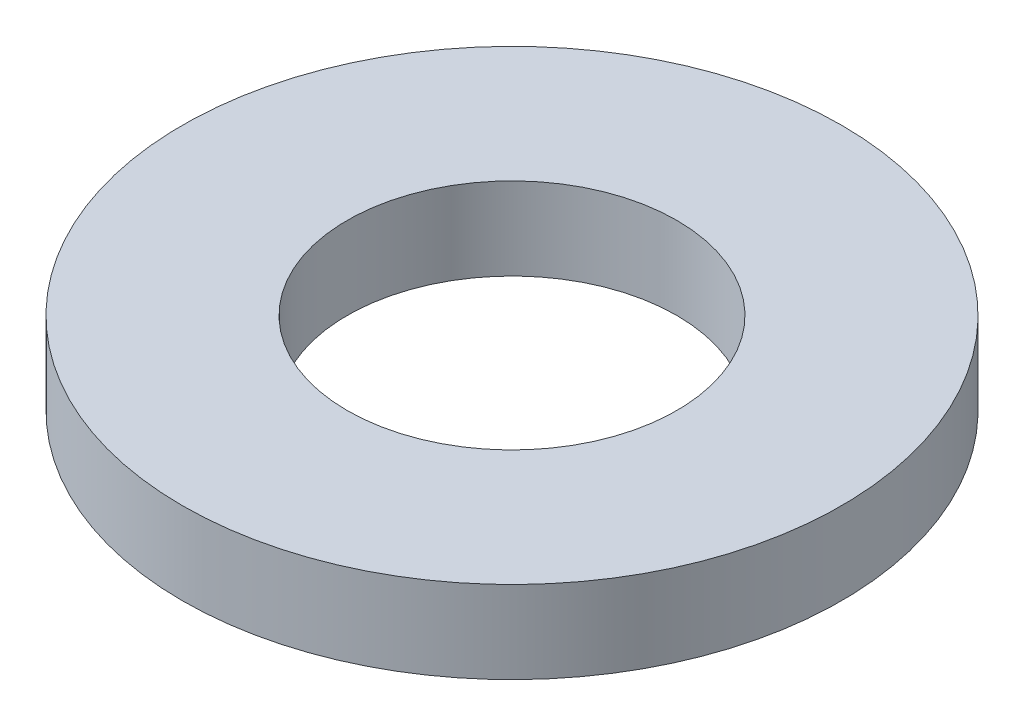
SolidWorks part; units mm, degrees
material "尼龙 101"
ref_plane "前视基准面" through (0, 0, 0) normal (0, 0, 1) x (1, 0, 0)
ref_plane "上视基准面" through (0, 0, 0) normal (0, 1, 0) x (1, 0, 0)
ref_plane "右视基准面" through (0, 0, 0) normal (1, 0, 0) x (0, 0, -1)
sketch "草图1" plane through (0, 0, 0) normal (0, 1, 0) x (1, 0, 0)
  circle A0 centre (0, 0) radius 3
  circle A1 centre (0, 0) radius 6
  dimension "D1" = 6
  dimension "D2" = 12
extrude "凸台-拉伸1" add sketch "草图1" along normal blind 1.5
